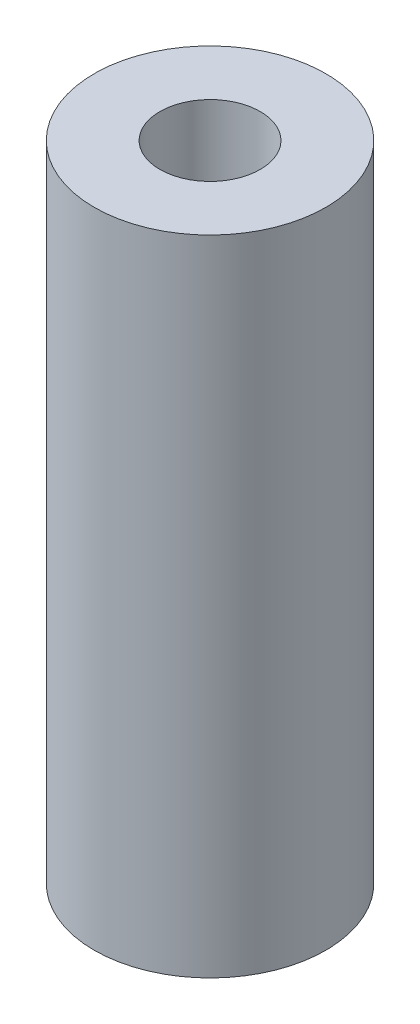
SolidWorks part; units mm, degrees
ref_plane "Front Plane" through (0, 0, 0) normal (0, 0, 1) x (1, 0, 0)
ref_plane "Top Plane" through (0, 0, 0) normal (0, 1, 0) x (1, 0, 0)
ref_plane "Right Plane" through (0, 0, 0) normal (1, 0, 0) x (0, 0, -1)
sketch "Sketch1" plane through (0, 0, 0) normal (0, 1, 0) x (1, 0, 0)
  circle A0 centre (0, 0) radius 4.5
  circle A1 centre (0, 0) radius 2.05
  dimension "D1" = 9
  dimension "D2" = 4.1
extrude "Boss-Extrude1" add sketch "Sketch1" along normal blind 10
sketch "Sketch3" plane through (0, 10, 0) normal (0, 1, 0) x (1, 0, 0)
  circle A1 centre (0, 0) radius 4.5
  circle A2 centre (0, 0) radius 1.95
  circle A3 centre (0, 0) radius 4.5 construction
  dimension "D1" = 3.9
extrude "Boss-Extrude3" add sketch "Sketch3" along normal blind 15
